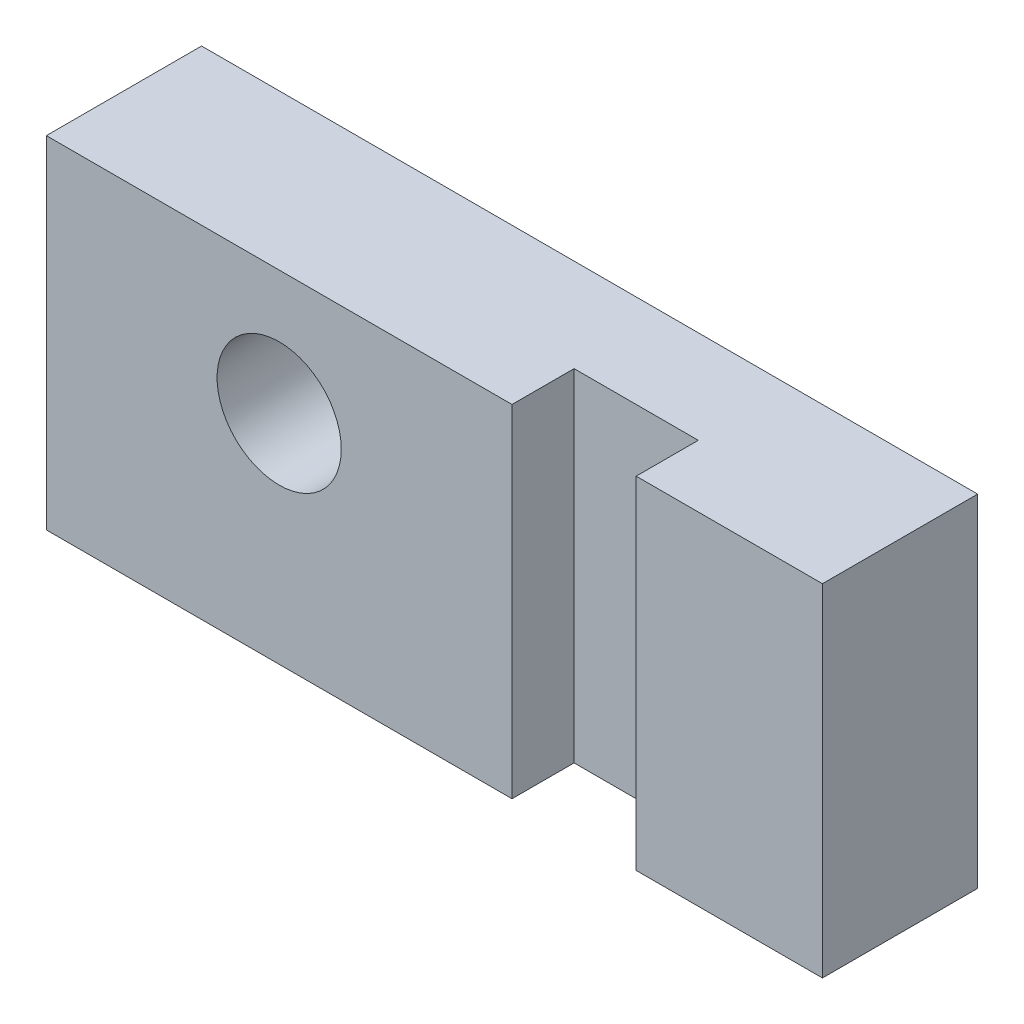
SolidWorks part; units mm, degrees
material "Сталь"
ref_plane "Спереди" through (0, 0, 0) normal (0, 0, 1) x (1, 0, 0)
ref_plane "Сверху" through (0, 0, 0) normal (0, 1, 0) x (1, 0, 0)
ref_plane "Справа" through (0, 0, 0) normal (1, 0, 0) x (0, 0, -1)
sketch "Эскиз1" plane through (0, 0, 0) normal (0, 0, 1) x (1, 0, 0)
  line L1 (-25, -11) -> (25, -11)
  line L2 (-25, -11) -> (-25, 11)
  line L3 (-25, 11) -> (25, 11)
  line L4 (25, -11) -> (25, 11)
  line L5 (-25, -11) -> (25, 11) construction
  line L6 (-25, 11) -> (25, -11) construction
  point P0 (0, 0)
  dimension "D1" = 22
  dimension "D2" = 50
extrude "Бобышка-Вытянуть1" add sketch "Эскиз1" along normal blind 10
sketch "Эскиз2" plane through (0, 0, 10) normal (0, 0, 1) x (1, 0, 0)
  line L0 (-25, 11) -> (-25, -11) construction
  line L1 (-25, -11) -> (25, -11) construction
  circle A0 centre (-10, 3) radius 4
  dimension "D1" = 8
  dimension "D2" = 15
  dimension "D3" = 14
extrude "Вырез-Вытянуть1" cut sketch "Эскиз2" against normal through all
sketch "Эскиз3" plane through (0, 0, 10) normal (0, 0, 1) x (1, 0, 0)
  line L0 (25, 11) -> (-25, 11) construction
  line L1 (5, 11) -> (13, 11)
  line L2 (5, 11) -> (5, -11)
  line L3 (5, -11) -> (13, -11)
  line L4 (13, 11) -> (13, -11)
  line L5 (-25, -11) -> (25, -11) construction
  line L6 (-25, 11) -> (-25, -11) construction
  dimension "D1" = 8
  dimension "D2" = 30
extrude "Вырез-Вытянуть2" cut sketch "Эскиз3" against normal blind 4
